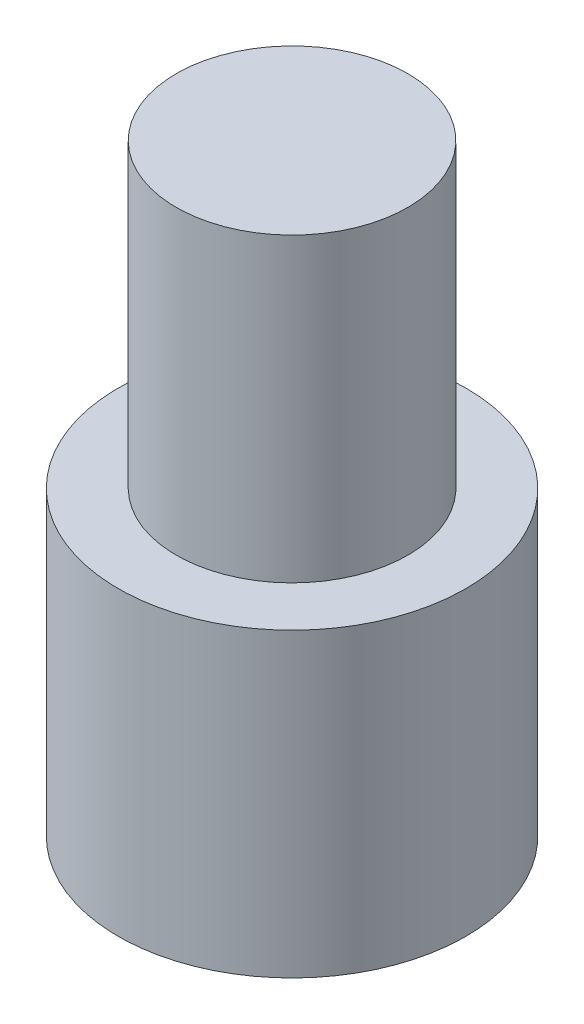
SolidWorks part; units mm, degrees
ref_plane "Front Plane" through (0, 0, 0) normal (0, 0, 1) x (1, 0, 0)
ref_plane "Top Plane" through (0, 0, 0) normal (0, 1, 0) x (1, 0, 0)
ref_plane "Right Plane" through (0, 0, 0) normal (1, 0, 0) x (0, 0, -1)
sketch "Sketch1" plane through (0, 0, 0) normal (0, 1, 0) x (1, 0, 0)
  circle A0 centre (-60.2153, 24.3554) radius 7.5
extrude "Boss-Extrude1" add sketch "Sketch1" along normal blind 13
sketch "Sketch2" plane through (0, 13, 0) normal (0, 1, 0) x (1, 0, 0)
  circle A0 centre (-60.2153, 24.3554) radius 5
extrude "Boss-Extrude2" add sketch "Sketch2" along normal blind 13
sketch "Sketch3" plane through (0, 0, 0) normal (0, -1, 0) x (1, 0, 0)
  circle A0 centre (-60.2153, -24.3554) radius 3
extrude "Cut-Extrude1" cut sketch "Sketch3" against normal blind 11
